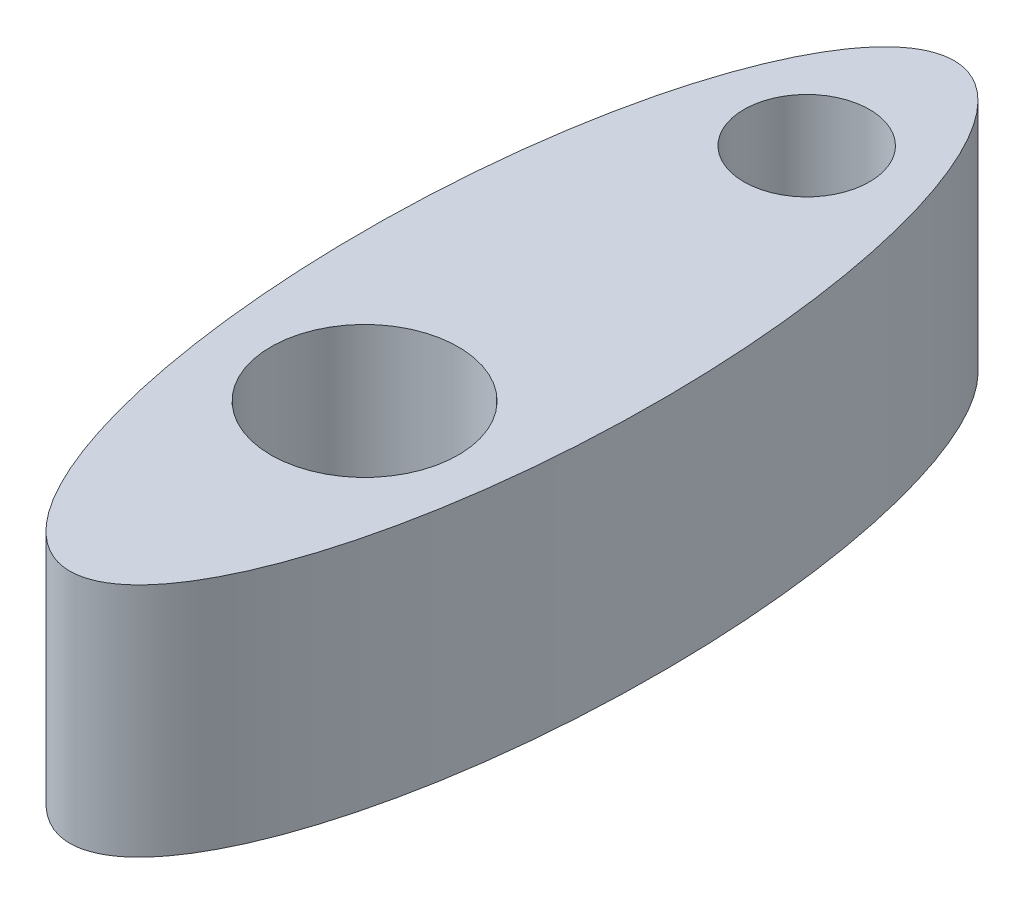
SolidWorks part; units mm, degrees
ref_plane "Front Plane" through (0, 0, 0) normal (0, 0, 1) x (1, 0, 0)
ref_plane "Top Plane" through (0, 0, 0) normal (0, 1, 0) x (1, 0, 0)
ref_plane "Right Plane" through (0, 0, 0) normal (1, 0, 0) x (0, 0, -1)
sketch "Sketch1" plane through (0, 0, 0) normal (0, 1, 0) x (1, 0, 0)
  circle A0 centre (0, 0) radius 15.875
  dimension "D1" = 31.75
extrude "Boss-Extrude1" add sketch "Sketch1" along normal blind 5.08
hole_wizard "#10-32 Tapped Hole1" positions "Sketch3" profile "Sketch4" tap size "#10-32" standard "ANSI Inch" end condition up to next
sketch "Sketch3" plane through (0, 5.08, 0) normal (0, 1, 0) x (1, 0, 0)
  point P0 (0, 0)
sketch "Sketch4" plane through (0, 5.08, 0) normal (1, 0, 0) x (0, 0, 1)
  line L0 (0, 0) -> (0, 5.08)
  line L1 (0, 5.08) -> (2.0193, 5.08)
  line L2 (2.0193, 5.08) -> (2.0193, 0)
  line L5 (2.0193, 0) -> (0, 0)
  line L11 (0, -6.35) -> (0, 107.95) construction
  dimension "Thru Tap Drill Dia." = 4.0386
  dimension "Thru Tap Drill Depth" = 5.08
cosmetic thread "Hole Thread1" parameters "D2"=4.826
hole_wizard "#6-32 Tapped Hole1" positions "Sketch6" profile "Sketch5" tap size "#6-32" standard "ANSI Inch" end condition up to next
sketch "Sketch6" plane through (0, 5.08, 0) normal (0, 1, 0) x (1, 0, 0)
  circle A0 centre (0, 0) radius 2.0193 construction
  point P0 (0, 9.525)
  dimension "D1" = 9.525
sketch "Sketch5" plane through (0, 5.08, -9.525) normal (1, 0, 0) x (0, 0, 1)
  line L0 (0, 0) -> (0, 5.08)
  line L1 (0, 5.08) -> (1.3525, 5.08)
  line L2 (1.3525, 5.08) -> (1.3525, 0)
  line L5 (1.3525, 0) -> (0, 0)
  line L11 (0, -6.35) -> (0, 107.95) construction
  dimension "Thru Tap Drill Dia." = 2.7051
  dimension "Thru Tap Drill Depth" = 5.08
cosmetic thread "Hole Thread2" parameters "D2"=3.5052
sketch "Sketch7" plane through (0, 5.08, 0) normal (0, 1, 0) x (1, 0, 0)
  ellipse E0 centre (0, 3.175) end of major axis (0, -6.35) minor radius 3.175
  dimension "D1" = 19.05
  dimension "D2" = 6.35
  dimension "D3" = 3.175
extrude "Cut-Extrude1" cut sketch "Sketch7" against normal through all flip side to cut
